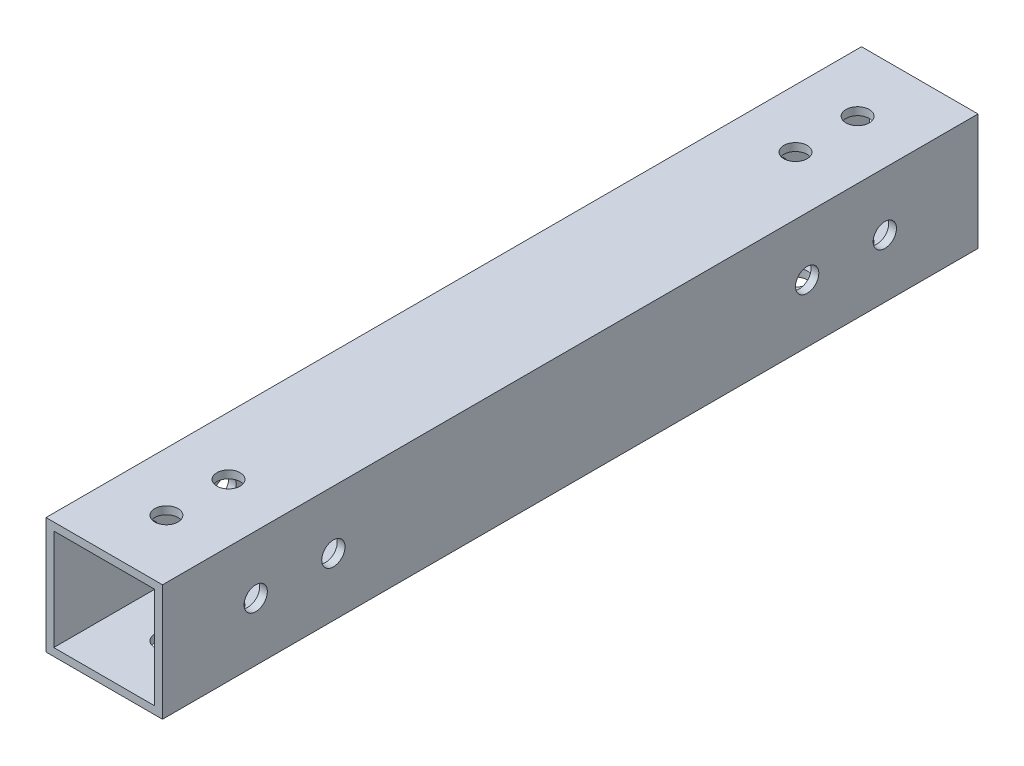
SolidWorks part; units mm, degrees
material "6061-O (SS)"
ref_plane "前视基准面" through (0, 0, 0) normal (0, 0, 1) x (1, 0, 0)
ref_plane "上视基准面" through (0, 0, 0) normal (0, 1, 0) x (1, 0, 0)
ref_plane "右视基准面" through (0, 0, 0) normal (1, 0, 0) x (0, 0, -1)
sketch "草图1" plane through (0, 0, 0) normal (0, 0, 1) x (1, 0, 0)
  line L1 (-6.5, -6.5) -> (6.5, -6.5)
  line L2 (-6.5, -6.5) -> (-6.5, 6.5)
  line L3 (-6.5, 6.5) -> (6.5, 6.5)
  line L4 (6.5, -6.5) -> (6.5, 6.5)
  line L5 (0, 6.5) -> (0, -6.5) construction
  line L6 (-6.5, 0) -> (6.5, 0) construction
  line L7 (-7.5, -7.5) -> (7.5, -7.5)
  line L8 (-7.5, -7.5) -> (-7.5, 7.5)
  line L9 (-7.5, 7.5) -> (7.5, 7.5)
  line L10 (7.5, -7.5) -> (7.5, 7.5)
  line L11 (0, 7.5) -> (0, -7.5) construction
  line L12 (-7.5, 0) -> (7.5, 0) construction
  point P0 (0, 0)
  point P4 (0, 0)
  dimension "D1" = 15
  dimension "D2" = 15
  dimension "D3" = 13
  dimension "D4" = 13
extrude "凸台-拉伸1" add sketch "草图1" along normal blind 105
sketch "草图3" plane through (0, 7.5, 0) normal (0, 1, 0) x (1, 0, 0)
  line L0 (-7.5, -105) -> (-7.5, 0) construction
  line L2 (7.5, -105) -> (-7.5, -105) construction
  line L3 (7.5, 0) -> (-7.5, 0) construction
  circle A0 centre (0, -97) radius 1.5
  circle A1 centre (0, -89) radius 1.5
  circle A2 centre (0, -16) radius 1.5
  circle A3 centre (0, -8) radius 1.5
  dimension "D4" = 3
  dimension "D1" = 7.5
  dimension "D2" = 8
  dimension "D3" = 8
  dimension "D5" = 8
  dimension "D6" = 8
  dimension "D7" = 7.5
extrude "切除-拉伸2" cut sketch "草图3" against normal through all
sketch "草图4" plane through (-7.5, 0, 0) normal (-1, 0, 0) x (0, 0, 1)
  line L0 (0, 7.5) -> (0, -7.5) construction
  line L1 (105, -7.5) -> (0, -7.5) construction
  line L2 (105, 7.5) -> (105, -7.5) construction
  circle A0 centre (93, 0) radius 1.5
  circle A1 centre (83, 0) radius 1.5
  circle A2 centre (12, 0) radius 1.5
  circle A3 centre (22, 0) radius 1.5
  dimension "D1" = 3
  dimension "D2" = 12
  dimension "D3" = 10
  dimension "D4" = 7.5
  dimension "D5" = 12
  dimension "D6" = 10
extrude "切除-拉伸3" cut sketch "草图4" against normal through all
